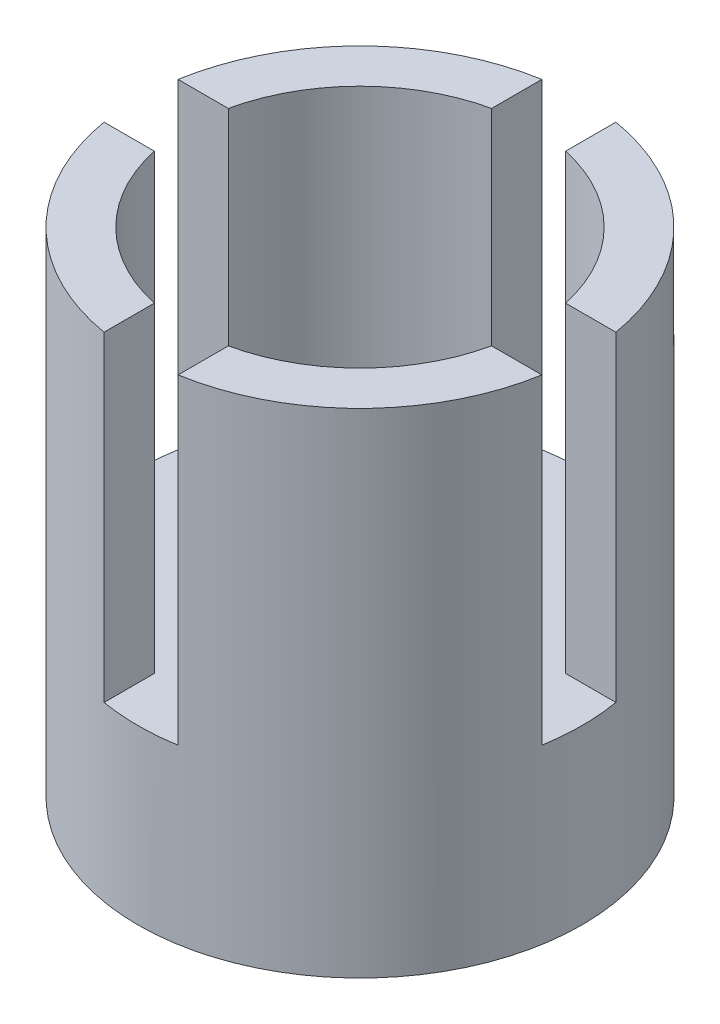
SolidWorks part; units mm, degrees
ref_plane "前视基准面" through (0, 0, 0) normal (0, 0, 1) x (1, 0, 0)
ref_plane "上视基准面" through (0, 0, 0) normal (0, 1, 0) x (1, 0, 0)
ref_plane "右视基准面" through (0, 0, 0) normal (1, 0, 0) x (0, 0, -1)
sketch "草图1" plane through (0, 0, 0) normal (0, 1, 0) x (1, 0, 0)
  circle A0 centre (0, 0) radius 9
  dimension "D1" = 18
extrude "凸台-拉伸1" add sketch "草图1" along normal blind 20
sketch "草图2" plane through (0, 0, 0) normal (0, -1, 0) x (-1, 0, 0)
  line L0 (0, 0) -> (2, 0) construction
  line L1 (2.1213, 1.75) -> (-2.1213, 1.75)
  line L3 (2.1213, -1.75) -> (-2.1213, -1.75)
  line L4 (0, 1.75) -> (0, 0) construction
  line L5 (0, 0) -> (0, -1.75) construction
  arc A0 (2.1213, -1.75) -> (2.1213, 1.75) centre (0, 0) ccw
  arc A1 (-2.1213, 1.75) -> (-2.1213, -1.75) centre (0, 0) ccw
  dimension "D1" = 5.5
  dimension "D2" = 3.5
extrude "切除-拉伸1" cut sketch "草图2" against normal blind 7
sketch "草图3" plane through (0, 20, 0) normal (0, 1, 0) x (1, 0, 0)
  circle A0 centre (0, 0) radius 7
  dimension "D1" = 14
extrude "切除-拉伸2" cut sketch "草图3" against normal blind 13
ref_plane "基准面1" through (0, 17, 0) normal (0, 1, 0) x (1, 0, 0)
sketch "草图8" plane through (0, 20, 0) normal (0, 1, 0) x (1, 0, 0)
  line L0 (0, -10.8462) -> (0, 10.9357) construction
  line L1 (-1.5, -10.8462) -> (-1.5, 10.9357)
  line L2 (1.5, -10.8462) -> (1.5, 10.9357)
  arc A0 (-1.5, -10.8462) -> (1.5, -10.8462) centre (0, -10.8462) ccw
  arc A1 (1.5, 10.9357) -> (-1.5, 10.9357) centre (0, 10.9357) ccw
  point P3 (0, 0.0448)
  dimension "D1" = 3
extrude "切除-拉伸3" cut sketch "草图8" against normal blind 13
sketch "草图9" plane through (0, 20, 0) normal (0, 1, 0) x (1, 0, 0)
  line L0 (-9.1429, 0) -> (9.1717, 0) construction
  line L1 (-9.1429, 1.5) -> (9.1717, 1.5)
  line L2 (-9.1429, -1.5) -> (9.1717, -1.5)
  arc A0 (-9.1429, 1.5) -> (-9.1429, -1.5) centre (-9.1429, 0) ccw
  arc A1 (9.1717, -1.5) -> (9.1717, 1.5) centre (9.1717, 0) ccw
  point P3 (0.0144, 0)
  dimension "D1" = 3
extrude "切除-拉伸4" cut sketch "草图9" against normal up to surface (13 mm away) up to face at (0, 7, 0)
